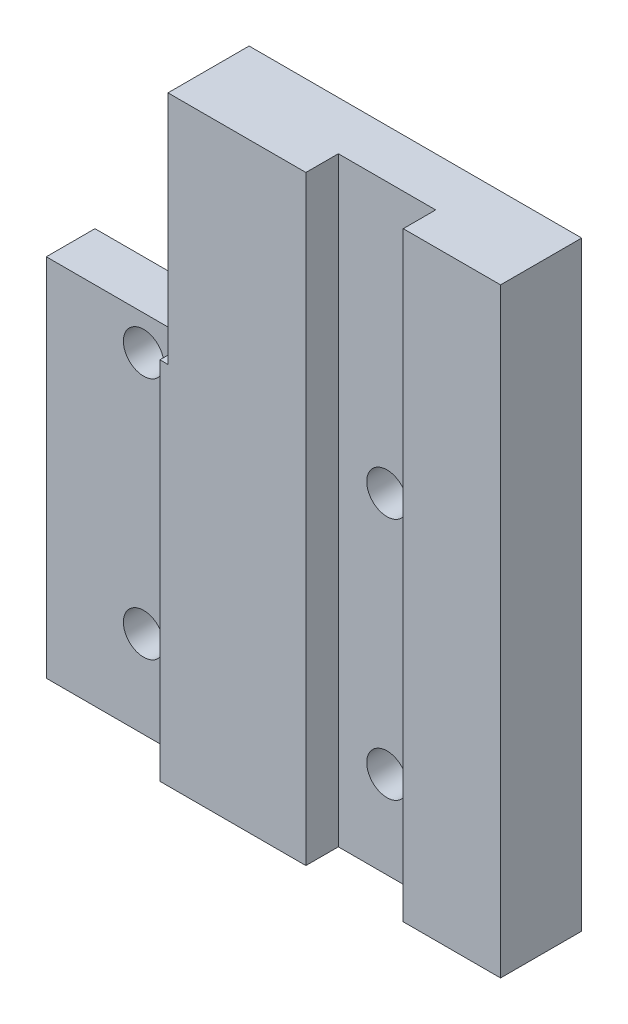
SolidWorks part; units mm, degrees
ref_plane "Front Plane" through (0, 0, 0) normal (0, 0, 1) x (1, 0, 0)
ref_plane "Top Plane" through (0, 0, 0) normal (0, 1, 0) x (1, 0, 0)
ref_plane "Right Plane" through (0, 0, 0) normal (1, 0, 0) x (0, 0, -1)
sketch "Sketch1" plane through (0, 0, 0) normal (0, 0, 1) x (1, 0, 0)
  line L0 (0, 0) -> (0, 45)
  line L1 (0, 45) -> (19, 45)
  line L2 (19, 45) -> (19, 74)
  line L3 (19, 74) -> (60, 74)
  line L4 (60, 74) -> (60, 0)
  line L5 (60, 0) -> (0, 0)
  dimension "D1" = 60
  dimension "D2" = 74
  dimension "D3" = 41
  dimension "D4" = 45
extrude "Boss-Extrude1" add sketch "Sketch1" along normal blind 6
sketch "Sketch2" plane through (0, 0, 6) normal (0, 0, 1) x (1, 0, 0)
  line L0 (0, 0) -> (60, 0) construction
  line L1 (60, 74) -> (48, 74)
  line L2 (60, 74) -> (60, 0)
  line L3 (60, 0) -> (48, 0)
  line L4 (48, 74) -> (48, 0)
  line L6 (19, 74) -> (36, 74)
  line L7 (19, 74) -> (19, 0)
  line L8 (19, 0) -> (36, 0)
  line L9 (36, 74) -> (36, 0)
  line L10 (19, 45) -> (18, 45)
  line L11 (19, 45) -> (19, 0)
  line L12 (19, 0) -> (18, 0)
  line L13 (18, 45) -> (18, 0)
  line M6 (0, 0) -> (60, 0)
  line M7 (60, 0) -> (60, 74)
  line M8 (60, 74) -> (19, 74)
  line M9 (19, 74) -> (19, 45)
  line M10 (19, 45) -> (0, 45)
  dimension "D1" = 12
  dimension "D2" = 12
  dimension "D3" = 1
extrude "Boss-Extrude2" add sketch "Sketch2" along normal blind 4 contours L9 L7 M8 M9 M6 | L4 M8 M6 M7 | L13 L7 M10 M6
hole_wizard "Ø5.0 (5) Diameter Hole1" positions "Sketch5" profile "Sketch4" hole size "Ø5.0" standard "ISO" end condition through all
sketch "Sketch5" plane through (0, 0, 6) normal (0, 0, 1) x (1, 0, 0)
  line L0 (36, 0) -> (48, 0) construction
  line L3 (36, 74) -> (36, 0) construction
  line L4 (36, 74) -> (36, 0) construction
  point P0 (42, 40.75)
  point P2 (42, 10.75)
  dimension "D1" = 30
  dimension "D2" = 10.75
  dimension "D3" = 6
  dimension "D4" = 6
sketch "Sketch4" plane through (42, 40.75, 6) normal (1, 0, 0) x (0, -1, 0)
  line L0 (0, 0) -> (0, 6)
  line L1 (0, 6) -> (2.5, 6)
  line L2 (2.5, 6) -> (2.5, 0)
  line L5 (2.5, 0) -> (0, 0)
  line L11 (0, -6.35) -> (0, 107.95) construction
  dimension "Thru Hole Dia." = 5
  dimension "Thru Hole Depth" = 6
hole_wizard "Ø5.0 (5) Diameter Hole2" positions "Sketch7" profile "Sketch6" hole size "Ø5.0" standard "ISO" end condition through all
sketch "Sketch7" plane through (0, 0, 6) normal (0, 0, 1) x (1, 0, 0)
  line L0 (0, 0) -> (18, 0) construction
  circle A0 centre (42, 40.75) radius 2.5 construction
  circle A1 centre (42, 10.75) radius 2.5 construction
  point P0 (12, 10.75)
  point P2 (12, 40.75)
  dimension "D1" = 10.75
  dimension "D2" = 30
  dimension "D3" = 30
  dimension "D4" = 30
sketch "Sketch6" plane through (12, 10.75, 6) normal (1, 0, 0) x (0, -1, 0)
  line L0 (0, 0) -> (0, 6)
  line L1 (0, 6) -> (2.5, 6)
  line L2 (2.5, 6) -> (2.5, 0)
  line L5 (2.5, 0) -> (0, 0)
  line L11 (0, -6.35) -> (0, 107.95) construction
  dimension "Thru Hole Dia." = 5
  dimension "Thru Hole Depth" = 6
